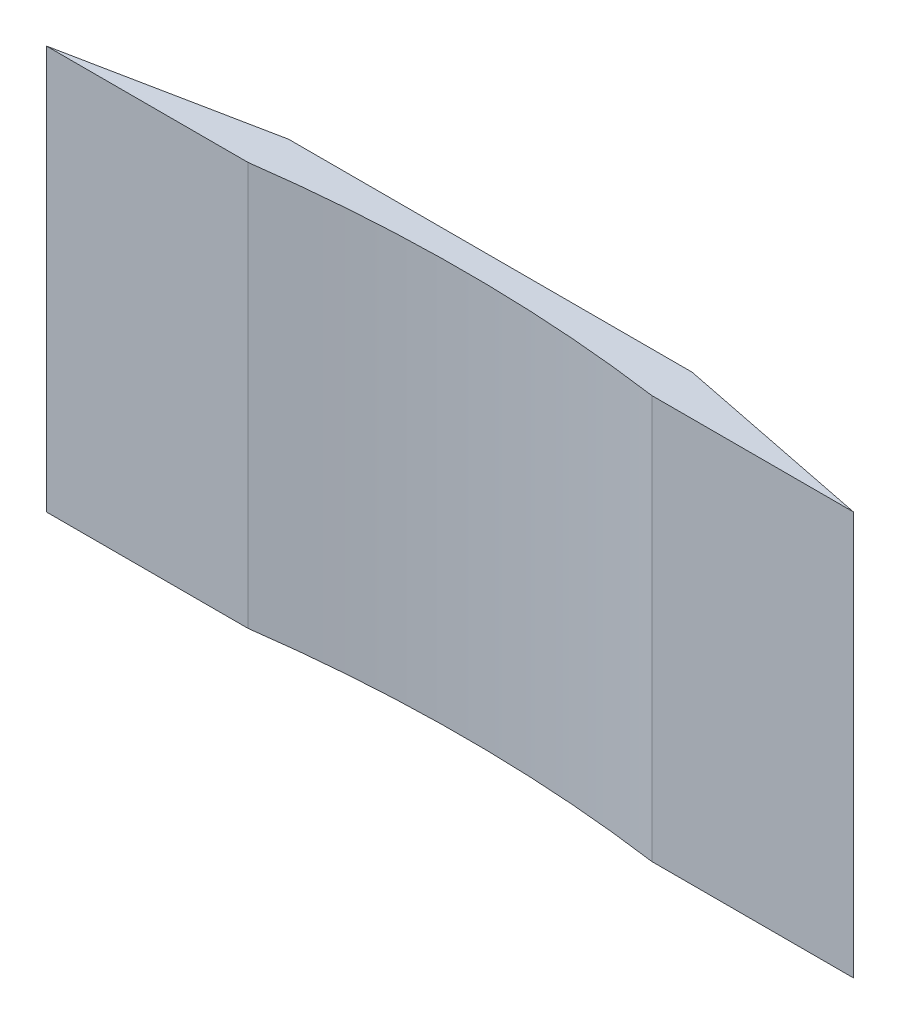
SolidWorks part; units mm, degrees
ref_plane "Płaszczyzna przednia" through (0, 0, 0) normal (0, 0, 1) x (1, 0, 0)
ref_plane "Płaszczyzna górna" through (0, 0, 0) normal (0, 1, 0) x (1, 0, 0)
ref_plane "Płaszczyzna prawa" through (0, 0, 0) normal (1, 0, 0) x (0, 0, -1)
sketch "Szkic1" plane through (0, 0, 0) normal (0, 1, 0) x (1, 0, 0)
  line L0 (-153.835, -33.2851) -> (-53.835, -33.2851)
  line L1 (246.165, -33.2851) -> (146.165, -13.2851)
  line L2 (146.165, -13.2851) -> (-53.835, -13.2851)
  line L3 (-53.835, -13.2851) -> (-153.835, -33.2851)
  line L4 (146.165, -33.2851) -> (246.165, -33.2851)
  arc A0 (-53.835, -33.2851) -> (146.165, -33.2851) centre (46.165, -755.0295) cw
  dimension "D1" = 400
  dimension "D2" = 200
  dimension "D4" = 100
  dimension "D5" = 100
extrude "Dodanie-wyciągnięcie1" add sketch "Szkic1" along normal blind 200
